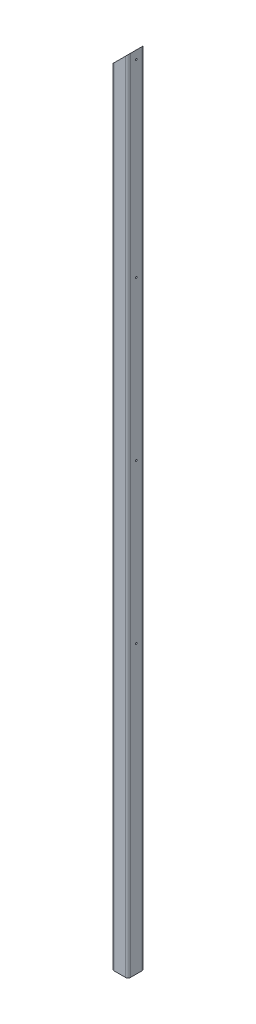
SolidWorks part; units mm, degrees
ref_plane "Front Plane" through (0, 0, 0) normal (0, 0, 1) x (1, 0, 0)
ref_plane "Top Plane" through (0, 0, 0) normal (0, 1, 0) x (1, 0, 0)
ref_plane "Right Plane" through (0, 0, 0) normal (1, 0, 0) x (0, 0, -1)
sketch "Sketch1" plane through (0, 0, 0) normal (0, 0, 1) x (1, 0, 0)
  line L0 (0, 0) -> (0, 1920)
  dimension "D1" = 1920
other "Tube (square) 40 X 40 X 3.2(1)"
ref_plane "Plane1" through (0, 0, 0) normal (0, 1, 0) x (-1, 0, 0)
sketch "Sketch15" plane through (0, 0, 0) normal (0, 1, 0) x (-1, 0, 0)
  line L0 (-13.6, -16.8) -> (13.6, -16.8)
  line L1 (-16.8, -13.6) -> (-16.8, 13.6)
  line L2 (13.6, 16.8) -> (-13.6, 16.8)
  line L3 (16.8, 13.6) -> (16.8, -13.6)
  line L4 (-13.6, -20) -> (13.6, -20)
  line L5 (-20, -13.6) -> (-20, 13.6)
  line L6 (13.6, 20) -> (-13.6, 20)
  line L7 (20, 13.6) -> (20, -13.6)
  line L8 (-20, 0) -> (-16.8, 0) construction
  line L9 (-16.8, 0) -> (16.8, 0) construction
  line L10 (16.8, 0) -> (20, 0) construction
  line L12 (0, 20) -> (0, 16.8) construction
  line L13 (0, 16.8) -> (0, -16.8) construction
  line L14 (0, -16.8) -> (0, -20) construction
  arc A0 (20, 13.6) -> (13.6, 20) centre (13.6, 13.6) ccw
  arc A1 (13.6, -20) -> (20, -13.6) centre (13.6, -13.6) ccw
  arc A2 (-20, -13.6) -> (-13.6, -20) centre (-13.6, -13.6) ccw
  arc A3 (-13.6, 20) -> (-20, 13.6) centre (-13.6, 13.6) ccw
  arc A4 (-13.6, 16.8) -> (-16.8, 13.6) centre (-13.6, 13.6) ccw
  arc A5 (16.8, 13.6) -> (13.6, 16.8) centre (13.6, 13.6) ccw
  arc A6 (13.6, -16.8) -> (16.8, -13.6) centre (13.6, -13.6) ccw
  arc A7 (-16.8, -13.6) -> (-13.6, -16.8) centre (-13.6, -13.6) ccw
  point P2 (-20, 20)
  point P33 (-20, -20)
  point P34 (20, -20)
  point P36 (20, 20)
  point P37 (0, 0)
  dimension "D1" = 6.4
  dimension "Thickness" = 3.2
  dimension "V_leg" = 40
  dimension "H_leg" = 40
ref_plane "Plane2" through (0, 0, -20) normal (0, 0, -1) x (-1, 0, 0)
sketch "Sketch13" plane through (0, 0, -20) normal (0, 0, -1) x (-1, 0, 0)
  line L2 (20, 1920) -> (20, 0) construction
  line L3 (20, 1920) -> (20, 1880)
  line L4 (-13.6, 1920) -> (13.6, 1920) construction
  line L5 (-20, 1920) -> (20, 1920)
  line L9 (20, 1880) -> (-20, 1920)
  line L10 (20, 1920) -> (20, 1880)
  dimension "D1" = 40
extrude "Cut-Extrude1" cut sketch "Sketch13" against normal through all contours L9 L3 L5
ref_plane "Plane3" through (20, 0, 0) normal (1, 0, 0) x (0, 0, -1)
sketch "Sketch16" plane through (20, 0, 0) normal (1, 0, 0) x (0, 0, -1)
  line L0 (-13.6, 1920) -> (13.6, 1920) construction
  line L1 (-13.6, 1920) -> (13.6, 1920) construction
  line L2 (-13.6, 1900) -> (13.6, 1900) construction
  line L3 (-13.6, 1447) -> (13.6, 1447) construction
  line L4 (-13.6, 1067) -> (13.6, 1067) construction
  line L5 (-13.6, 687) -> (13.6, 687) construction
  circle A0 centre (0, 1900) radius 2
  circle A1 centre (0, 1447) radius 2
  circle A2 centre (0, 1067) radius 2
  circle A3 centre (0, 687) radius 2
  dimension "D4" = 4
  dimension "D5" = 1233
  dimension "D1" = 20
  dimension "D2" = 453
  dimension "D3" = 833
extrude "Cut-Extrude2" cut sketch "Sketch16" against normal blind 3
ref_plane "Plane4" through (0, 0, -20) normal (0, 0, -1) x (-1, 0, 0)
sketch "Sketch17" plane through (0, 0, -20) normal (0, 0, -1) x (-1, 0, 0)
  line L0 (-13.6, 0) -> (13.6, 0) construction
  line L1 (-13.6, 0) -> (13.6, 0)
  line L2 (-13.6, 687) -> (13.6, 687) construction
  circle A0 centre (0, 687) radius 2
  dimension "D1" = 687
extrude "Cut-Extrude3" cut sketch "Sketch17" against normal blind 3 contours A0
